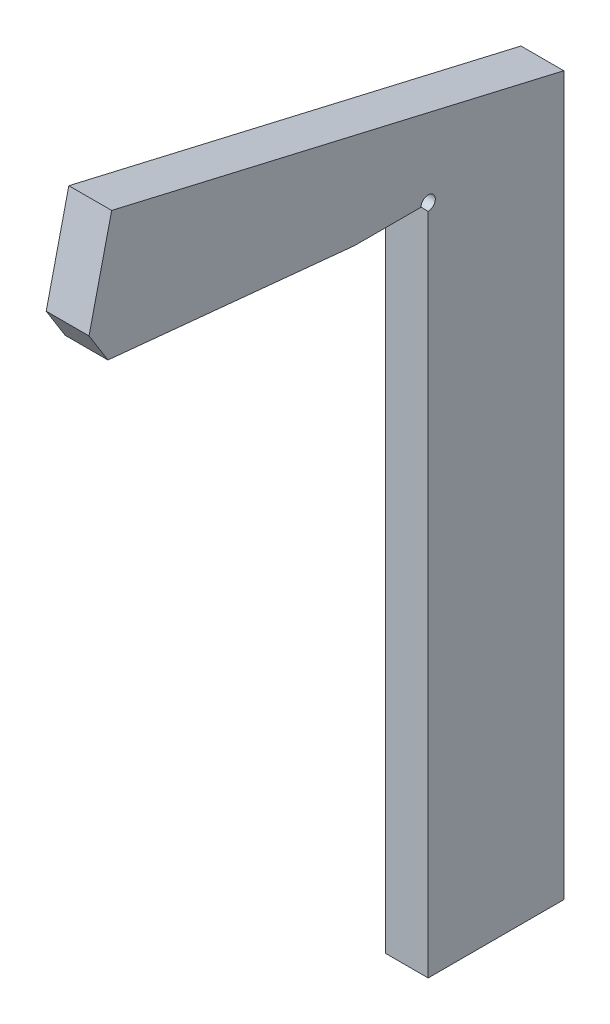
SolidWorks part; units mm, degrees
material "MDF"
ref_plane "Front Plane" through (0, 0, 0) normal (0, 0, 1) x (1, 0, 0)
ref_plane "Top Plane" through (0, 0, 0) normal (0, 1, 0) x (1, 0, 0)
ref_plane "Right Plane" through (0, 0, 0) normal (1, 0, 0) x (0, 0, -1)
sketch "Sketch2" plane through (-113.7888, 0, 0) normal (1, 0, 0) x (0, 0, -1)
  line L17 (0, 20.8246) -> (-83.8286, 40.3069)
  line L18 (0, 20.8246) -> (-83.8286, 40.3069)
  line L29 (-83.8286, 40.3069) -> (-93.1962, 0)
  line L30 (-83.8286, 40.3069) -> (-93.1962, 0)
  line L31 (-93.1962, 0) -> (-63.5, 0)
  line L32 (-93.1962, 0) -> (-63.5, 0)
  line L46 (0, -298.45) -> (-60.325, -298.45)
  line L47 (0, -363.22) -> (0, -433.07) construction
  line L48 (-28.575, -298.45) -> (0, -298.45) construction
  line L53 (-28.575, -447.675) -> (-28.575, -450.85)
  line L54 (-28.575, -450.85) -> (0, -450.85)
  line L55 (0, -450.85) -> (0, 20.8246)
  line L57 (-60.325, -3.175) -> (-60.325, -412.75)
  line L60 (0, -298.45) -> (0, 20.8246)
  line L62 (-60.325, -3.175) -> (-60.325, -298.45)
  arc A14 (-60.325, -3.175) -> (-63.5, 0) centre (-60.325, 0) ccw
  arc A15 (-60.325, -412.75) -> (-31.746, -444.3413) centre (-28.575, -412.75) ccw
  arc A16 (-28.575, -447.675) -> (-31.746, -444.3413) centre (-28.575, -444.5) ccw
  arc A17 (-60.325, -3.175) -> (-63.5, 0) centre (-60.325, 0) ccw
  point P5 (0, 0)
  point P10 (0, 16.2503)
  dimension "D2" = 0
extrude "Boss-Extrude1" add sketch "Sketch2" along normal blind 19.05
sketch "Sketch3" plane through (-113.7888, 0, 0) normal (-1, 0, 0) x (0, 0, 1)
  line L0 (83.8286, 40.3069) -> (201.0857, 67.5582)
  line L1 (495.3358, 135.9439) -> (66.675, 36.3203) construction
  line L2 (201.0857, 67.5582) -> (214.0229, 11.8918)
  line L7 (83.8286, 40.3069) -> (93.1962, 0)
  line L8 (93.1962, 0) -> (214.0229, 11.8918)
  arc A0 (63.5, 0) -> (60.325, -3.175) centre (60.325, 0) ccw construction
  dimension "D1" = 57.15
  dimension "D2" = 152.4
extrude "Boss-Extrude2" add sketch "Sketch3" against normal through all
chamfer "Chamfer1" distance 12.7 angle 45 1 edges at (-104.2638, 11.8918, 214.0229)
